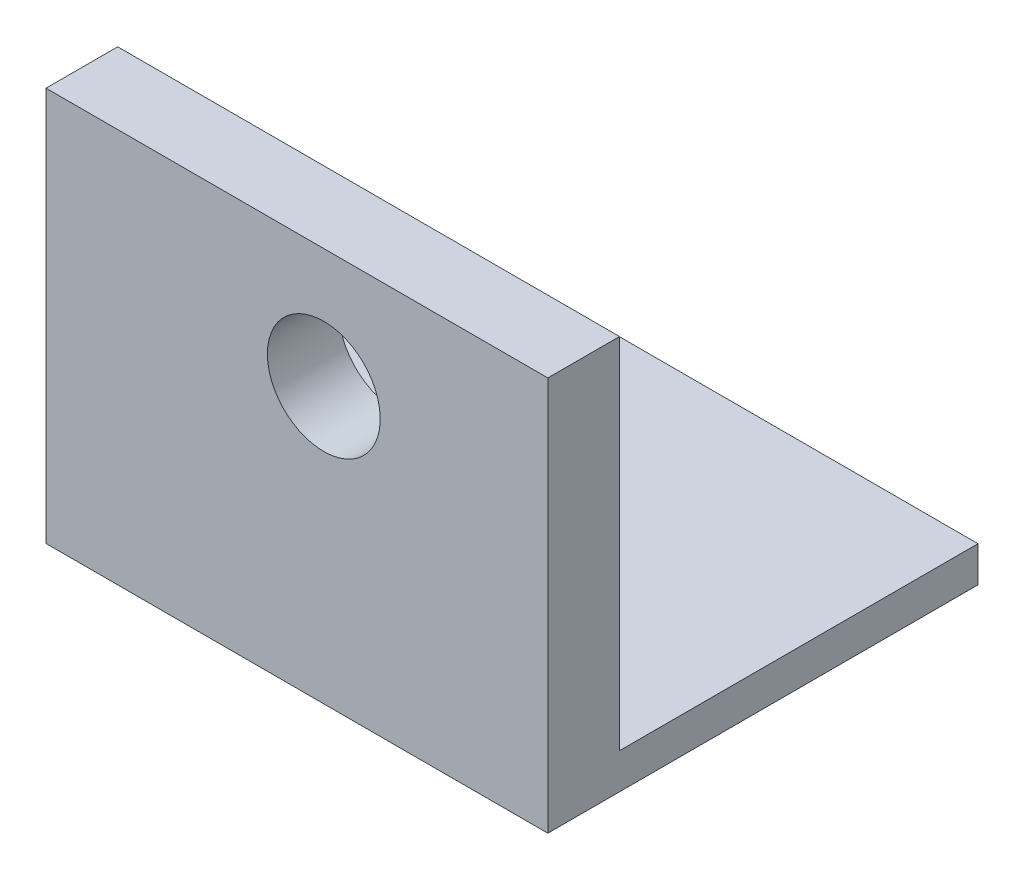
SolidWorks part; units mm, degrees
ref_plane "Front Plane" through (0, 0, 0) normal (0, 0, 1) x (1, 0, 0)
ref_plane "Top Plane" through (0, 0, 0) normal (0, 1, 0) x (1, 0, 0)
ref_plane "Right Plane" through (0, 0, 0) normal (1, 0, 0) x (0, 0, -1)
sketch "Sketch1" plane through (0, 0, 0) normal (0, 0, 1) x (1, 0, 0)
  line L1 (0, 0) -> (140, 0)
  line L2 (0, 0) -> (0, 110)
  line L3 (0, 110) -> (140, 110)
  line L4 (140, 0) -> (140, 110)
  dimension "D1" = 140
  dimension "D2" = 110
extrude "Boss-Extrude1" add sketch "Sketch1" along normal blind 120
sketch "Sketch2" plane through (0, 0, 0) normal (0, 0, -1) x (-1, 0, 0)
  line L0 (-140, 9.9475) -> (0, 9.9475)
  line L1 (-140, 0) -> (-140, 110) construction
  line L2 (0, 110) -> (0, 0) construction
extrude "Cut-Extrude1" cut sketch "Sketch2" against normal blind 100 and the other way through all
sketch "Sketch3" plane through (0, 0, 100) normal (0, 0, -1) x (-1, 0, 0)
  line L1 (-140, 110) -> (0, 110)
  line L2 (-140, 110) -> (-140, 9.9475)
  line L3 (-140, 9.9475) -> (0, 9.9475)
  line L4 (0, 110) -> (0, 9.9475)
  circle A0 centre (-77.4978, 76.7016) radius 15.7394
extrude "Cut-Extrude2" cut sketch "Sketch3" against normal through all contours A0
